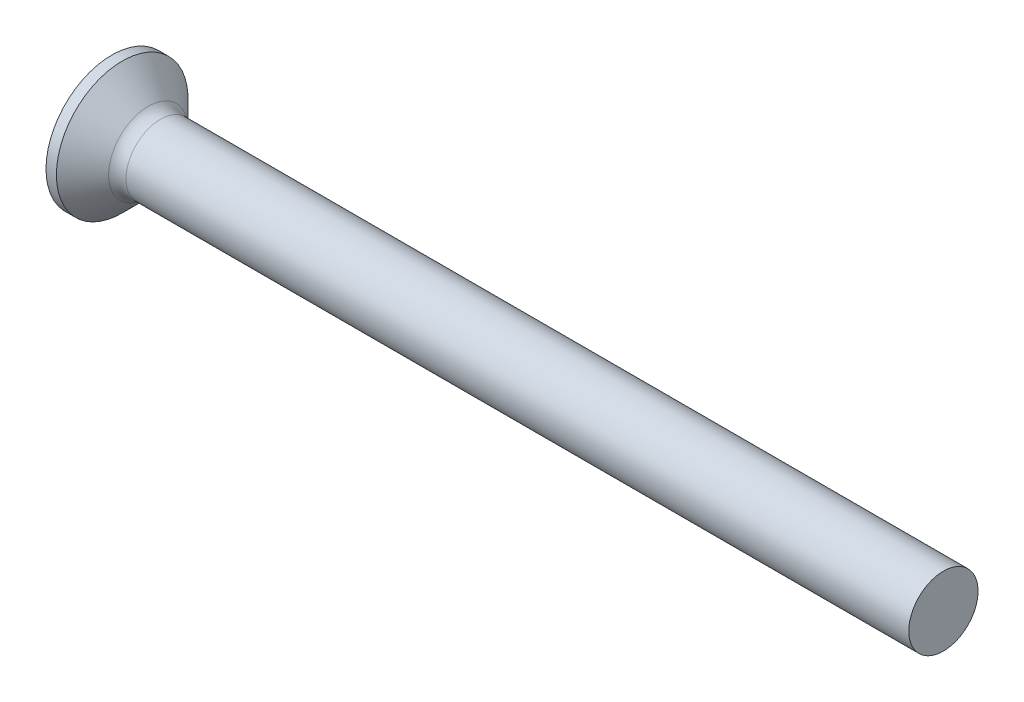
SolidWorks part; units mm, degrees
ref_plane "Plane1" through (0, 0, 0) normal (0, 0, 1) x (1, 0, 0)
ref_plane "Plane2" through (0, 0, 0) normal (0, 1, 0) x (1, 0, 0)
ref_plane "Plane3" through (0, 0, 0) normal (1, 0, 0) x (0, 0, -1)
sketch "BodySke" plane through (0, 0, 0) normal (0, 0, 1) x (1, 0, 0)
  line L0 (0, 0) -> (0, 1.9)
  line L1 (0, 1.9) -> (0.3, 1.9)
  line L2 (1.2, 1) -> (24, 1)
  line L3 (24, 1) -> (24, 0)
  line L4 (24, 0) -> (0, 0)
  line L5 (-6.35, 0) -> (82.55, 0) construction
  line L6 (1.2, -1) -> (24, -1) construction
  line L7 (0.3, -1.9) -> (1.2, -1) construction
  line L8 (0.3, 1.9) -> (1.2, 1)
  line L9 (0, -1.9) -> (0.3, -1.9) construction
  line L10 (1.6, 2.5875) -> (1.6, -6.9375) construction
  line L11 (4, 6.35) -> (4, -3.175) construction
  dimension "Diameter" = 2
  dimension "Length" = 24
  dimension "Head_ht" = 1.2
  dimension "Head_dia" = 3.8
  dimension "Head_ang" = 90
  dimension "D6" = 0.3
  dimension "Advance" = 0.4
  dimension "Thread_nom" = 20
revolve "Base-Revolve" add sketch "BodySke"
cosmetic thread "ThreadCosmetic" [suppressed]
fillet "Fillet1" radius 0.5 1 edges at (1.2, 0, 1)
sketch "Sketch3" plane through (0, 0, 0) normal (-1, 0, 0) x (0, 0, 1)
  line L0 (-0.24, 0.95) -> (0.24, 0.95)
  line L1 (0.24, 0.95) -> (0.24, -0.95)
  line L2 (0.24, -0.95) -> (-0.24, -0.95)
  line L3 (-0.24, -0.95) -> (-0.24, 0.95)
  dimension "D1" = 0.95
  dimension "Cross_dia" = 1.9
  dimension "D2" = 0.24
  dimension "Cross_width" = 0.48
ref_plane "Plane4" through (1.2, 0, 0) normal (-1, 0, 0) x (0, 0, 1)
sketch "Sketch4" plane through (1.2, 0, 0) normal (-1, 0, 0) x (0, 0, 1)
  line L0 (-0.24, 0.3517) -> (0.24, 0.3517)
  line L3 (0.24, 0.3517) -> (0.24, -0.3517)
  line L4 (0.24, -0.3517) -> (-0.24, -0.3517)
  line L5 (-0.24, -0.3517) -> (-0.24, 0.3517)
  dimension "D1" = 0.48
  dimension "D2" = 0.7034
  dimension "D3" = 0.24
  dimension "D4" = 0.3517
loft "Recess" cut profiles "Sketch3", "Sketch4"
pattern_circular "RecPat" count 2 every 90 about axis through (0, 0, 0) along (1, 0, 0) of "Recess"
sketch "RecCorSke" plane through (0, 0, 0) normal (0, 0, 1) x (1, 0, 0)
  line L0 (-3.175, 0) -> (15.875, 0) construction
  line L2 (0, 0) -> (0, 0.4394)
  line L3 (0, 0.4394) -> (1.2, 0.3555)
  line L4 (1.2, 0.3555) -> (1.3155, 0)
  line L5 (1.3155, 0) -> (0, 0)
  dimension "Diameter" = 0.711
  dimension "Depth" = 1.2
  dimension "Draft_angle" = 4
  dimension "Bottom_angle" = 18
revolve "RecessCore" cut sketch "RecCorSke" angle 360 about L0
sketch "ThdSchSke" plane through (0, 0, 0) normal (0, 0, 1) x (1, 0, 0)
  line L0 (4, -0.774) -> (3.8418, -1)
  line L1 (4, -0.774) -> (4.1582, -1)
  line L2 (4.1582, -1) -> (4.1582, -1.25)
  line L3 (-3.175, 0) -> (5.1513, 0) construction
  line L5 (4.1582, -1.25) -> (3.8418, -1.25)
  line L6 (3.8418, -1.25) -> (3.8418, -1)
  line L7 (0, 1.9) -> (0, -1.9) construction
  dimension "Thread_minor" = 1.548
  dimension "Diameter" = 2
  dimension "Start" = 4
  dimension "SideAngle" = 55
  dimension "VeeAngle" = 70
  dimension "Overcut" = 2.5
revolve "ThreadSchematic" [suppressed] cut sketch "ThdSchSke" angle 360 about L3
pattern_linear "ThdSchPat" [suppressed]
equation "\"D1@Sketch3\" = \"Cross_dia@Sketch3\" / 2"
equation "\"D2@Sketch3\" = \"Cross_width@Sketch3\" / 2"
equation "\"Depth@RecCorSke\" = \"Cross_depth@Plane4\""
equation "\"D1@Sketch4\" = \"Cross_width@Sketch3\""
equation "\"D2@Sketch4\" = \"Cross_dia@Sketch3\" - 2.0 * \"Cross_depth@Plane4\" * tan(26.5  * 0.017453292)"
equation "\"D3@Sketch4\" = \"D1@Sketch4\" / 2"
equation "\"D4@Sketch4\" = \"D2@Sketch4\" / 2"
equation "\"Thread_length@ThreadCosmetic\" = ((sgn( (\"Length@BodySke\" - \"Advance@BodySke\" * 1.0 - \"Head_ht@BodySke\" ) - \"Thread_nom@BodySke\" )-1)*( (\"Length@BodySke\" - \"Advance@BodySke\" * 1.0 - \"Head_ht@BodySke\" ) - \"Thread_nom@BodySke\" ))/-2+ \"Thread_nom@BodySke\""
equation "\"Thread_minor@ThdSchSke\" = \"Thread_minor@ThreadCosmetic\""
equation "\"Diameter@ThdSchSke\" = \"Diameter@BodySke\""
equation "\"Overcut@ThdSchSke\" = \"Diameter@BodySke\" * 1.25"
equation "\"Start@ThdSchSke\" = 0.000001 + \"Length@BodySke\" - \"Thread_length@ThreadCosmetic\"  '---Countersunk---"
equation "\"Num_threads@ThdSchPat\" = int( \"Thread_length@ThreadCosmetic\" / \"Advance@BodySke\" + 0.999 )  + 1"
equation "\"Advance@ThdSchPat\" = \"Thread_length@ThreadCosmetic\" /  (\"Num_threads@ThdSchPat\" - 1) 'relax it"
